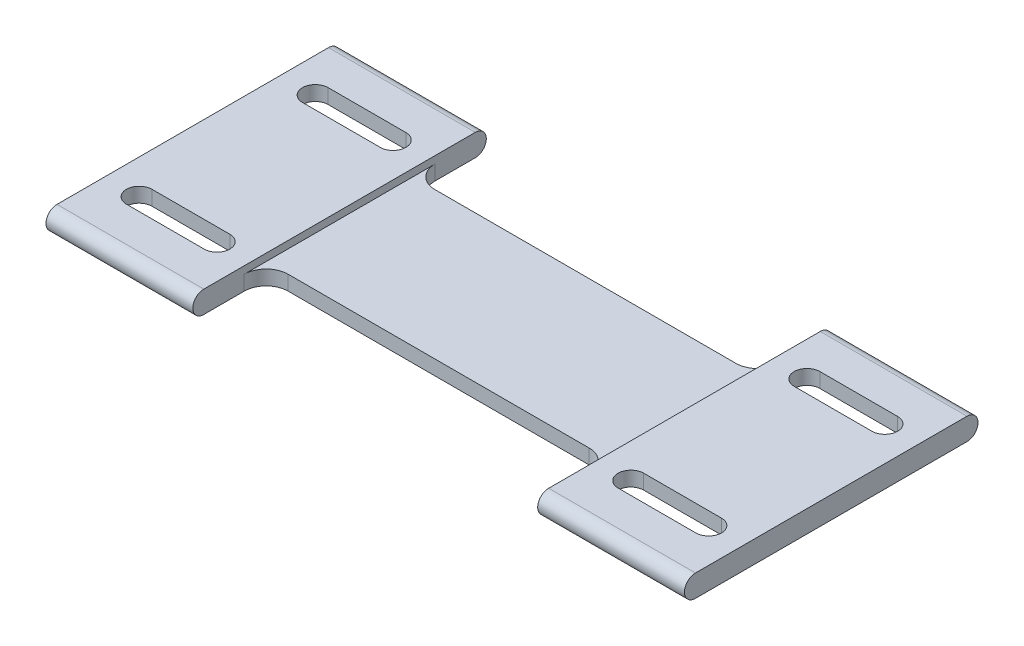
SolidWorks part; units mm, degrees
ref_plane "前视基准面" through (0, 0, 0) normal (0, 0, 1) x (1, 0, 0)
ref_plane "上视基准面" through (0, 0, 0) normal (0, 1, 0) x (1, 0, 0)
ref_plane "右视基准面" through (0, 0, 0) normal (1, 0, 0) x (0, 0, -1)
sketch "草图1" plane through (0, 0, 0) normal (0, 1, 0) x (1, 0, 0)
  line L1 (-43.5, -18.5) -> (43.5, -18.5) construction
  line L2 (-43.5, -18.5) -> (-43.5, 18.5) construction
  line L3 (-43.5, 18.5) -> (43.5, 18.5) construction
  line L4 (43.5, -18.5) -> (43.5, 18.5) construction
  line L5 (-43.5, -18.5) -> (43.5, 18.5) construction
  line L6 (-43.5, 18.5) -> (43.5, -18.5) construction
  point P0 (0, 0)
  dimension "D1" = 87
  dimension "D2" = 37
sketch "草图2" plane through (0, 0, 0) normal (1, 0, 0) x (0, 0, -1)
  line L0 (-18.5, 0) -> (18.5, 0) construction
  line L1 (-18.5, 0) -> (18.5, 0) construction
  line L2 (-18.5, 0) -> (18.5, 0) construction
  line L3 (18.5, 0) -> (-18.5, 0) construction
  line L4 (-18.5, 1.5) -> (18.5, 1.5)
  line L5 (-18.5, -1.5) -> (18.5, -1.5)
  arc A0 (-18.5, 1.5) -> (-18.5, -1.5) centre (-18.5, 0) ccw
  arc A1 (18.5, -1.5) -> (18.5, 1.5) centre (18.5, 0) ccw
  point P8 (0, 0)
  dimension "D1" = 1.5
extrude "凸台-拉伸1" add sketch "草图2" along normal mid plane 87
sketch "草图3" plane through (0, 1.5, 0) normal (0, 1, 0) x (1, 0, 0)
  line L0 (43.5, 20) -> (-43.5, 20) construction
  line L1 (-23.5, -20) -> (23.5, -20)
  line L2 (-23.5, -20) -> (-23.5, 20)
  line L3 (-23.5, 20) -> (23.5, 20)
  line L4 (23.5, -20) -> (23.5, 20)
  line L5 (-23.5, -20) -> (23.5, 20) construction
  line L6 (-23.5, 20) -> (23.5, -20) construction
  line L7 (-43.5, -18.5) -> (-43.5, 18.5) construction
  point P0 (0, 0)
  dimension "D1" = 20
extrude "切除-拉伸1" cut sketch "草图3" against normal blind 1
sketch "草图4" plane through (0, 0.5, 0) normal (0, 1, 0) x (1, 0, 0)
  line L0 (-43.5, -18.5) -> (43.5, 18.5) construction
  line L1 (-23.5, 9.9943) -> (23.5, 9.9943)
  line L2 (-23.5, 9.9943) -> (-23.5, 26.0227)
  line L3 (-23.5, 26.0227) -> (23.5, 26.0227)
  line L4 (23.5, 9.9943) -> (23.5, 26.0227)
  line L5 (-23.5, 9.9943) -> (23.5, 26.0227) construction
  line L6 (-23.5, 26.0227) -> (23.5, 9.9943) construction
  line L7 (-23.5, 0) -> (23.5, 0) construction
  line L8 (-23.5, -18.5) -> (-23.5, 18.5) construction
  line L9 (23.5, 18.5) -> (23.5, -18.5) construction
  line L10 (-23.5, -26.0227) -> (23.5, -9.9943) construction
  line L11 (-23.5, -9.9943) -> (23.5, -26.0227) construction
  line L12 (23.5, -9.9943) -> (23.5, -26.0227)
  line L13 (-23.5, -26.0227) -> (23.5, -26.0227)
  line L14 (-23.5, -9.9943) -> (-23.5, -26.0227)
  line L15 (-23.5, -9.9943) -> (23.5, -9.9943)
  line L16 (23.5, -19.9142) -> (23.5, 19.9142) construction
  line L17 (-23.5, 19.9142) -> (-23.5, -19.9142) construction
  point P0 (0, 18.0085)
  point P18 (0, -18.0085)
extrude "切除-拉伸2" cut sketch "草图4" against normal through all
sketch "草图5" plane through (0, -1.5, 0) normal (0, -1, 0) x (-1, 0, 0)
  line L0 (38.8, -12) -> (28.2, -12) construction
  line L1 (38.8, -13.75) -> (28.2, -13.75)
  line L2 (38.8, -10.25) -> (28.2, -10.25)
  line L3 (23.5, -20) -> (43.5, -20) construction
  line L4 (43.5, -18.5) -> (43.5, 18.5) construction
  line L5 (23.5, -9.9943) -> (23.5, -18.5) construction
  line L6 (43.5, 0) -> (-43.5, 0) construction
  line L7 (-43.5, -18.5) -> (-43.5, 18.5) construction
  line L8 (38.8, 12) -> (28.2, 12) construction
  line L9 (38.8, 13.75) -> (28.2, 13.75)
  line L10 (38.8, 10.25) -> (28.2, 10.25)
  line L11 (0, -9.9943) -> (0, 9.9943) construction
  line L12 (-23.5, -9.9943) -> (23.5, -9.9943) construction
  line L13 (23.5, 9.9943) -> (-23.5, 9.9943) construction
  line L14 (-38.8, 12) -> (-28.2, 12) construction
  line L15 (-38.8, 13.75) -> (-28.2, 13.75)
  line L16 (-38.8, 10.25) -> (-28.2, 10.25)
  line L17 (-38.8, -12) -> (-28.2, -12) construction
  line L18 (-38.8, -13.75) -> (-28.2, -13.75)
  line L19 (-38.8, -10.25) -> (-28.2, -10.25)
  arc A0 (38.8, -13.75) -> (38.8, -10.25) centre (38.8, -12) ccw
  arc A1 (28.2, -10.25) -> (28.2, -13.75) centre (28.2, -12) ccw
  arc A2 (38.8, 13.75) -> (38.8, 10.25) centre (38.8, 12) cw
  arc A3 (28.2, 10.25) -> (28.2, 13.75) centre (28.2, 12) cw
  arc A4 (-38.8, 13.75) -> (-38.8, 10.25) centre (-38.8, 12) ccw
  arc A5 (-28.2, 10.25) -> (-28.2, 13.75) centre (-28.2, 12) ccw
  arc A6 (-38.8, -13.75) -> (-38.8, -10.25) centre (-38.8, -12) cw
  arc A7 (-28.2, -10.25) -> (-28.2, -13.75) centre (-28.2, -12) cw
  point P2 (33.5, -12)
  point P19 (33.5, 12)
  point P32 (-33.5, 12)
  point P39 (-33.5, -12)
  dimension "D1" = 1.75
  dimension "D2" = 8
  dimension "D3" = 4.7
  dimension "D4" = 4.7
extrude "切除-拉伸3" cut sketch "草图5" against normal through all
sketch "草图6" plane through (0, -1.5, 0) normal (0, -1, 0) x (1, 0, 0)
  line L0 (-28.2, 15.75) -> (-38.8, 15.75)
  line L1 (-38.8, 8.25) -> (-28.2, 8.25)
  line L2 (-28.2, 13.75) -> (-38.8, 13.75)
  line L3 (-38.8, 10.25) -> (-28.2, 10.25)
  line L4 (-28.2, 13.75) -> (-38.8, 13.75) construction
  line L5 (-38.8, 10.25) -> (-28.2, 10.25) construction
  line L6 (-38.8, -13.75) -> (-28.2, -13.75)
  line L7 (-28.2, -10.25) -> (-38.8, -10.25)
  line L8 (-38.8, -13.75) -> (-28.2, -13.75) construction
  line L9 (-28.2, -10.25) -> (-38.8, -10.25) construction
  line L10 (38.8, 13.75) -> (28.2, 13.75)
  line L11 (28.2, 10.25) -> (38.8, 10.25)
  line L12 (38.8, 13.75) -> (28.2, 13.75) construction
  line L13 (28.2, 10.25) -> (38.8, 10.25) construction
  line L14 (28.2, -13.75) -> (38.8, -13.75)
  line L15 (38.8, -10.25) -> (28.2, -10.25)
  line L16 (28.2, -13.75) -> (38.8, -13.75) construction
  line L17 (38.8, -10.25) -> (28.2, -10.25) construction
  line L18 (-38.8, -15.75) -> (-28.2, -15.75)
  line L19 (-28.2, -8.25) -> (-38.8, -8.25)
  line L20 (38.8, 15.75) -> (28.2, 15.75)
  line L21 (28.2, 8.25) -> (38.8, 8.25)
  line L22 (28.2, -15.75) -> (38.8, -15.75)
  line L23 (38.8, -8.25) -> (28.2, -8.25)
  arc A0 (-38.8, 15.75) -> (-38.8, 8.25) centre (-38.8, 12) ccw
  arc A1 (-28.2, 8.25) -> (-28.2, 15.75) centre (-28.2, 12) ccw
  arc A2 (-28.2, 10.25) -> (-28.2, 13.75) centre (-28.2, 12) ccw
  arc A3 (-38.8, 13.75) -> (-38.8, 10.25) centre (-38.8, 12) ccw
  arc A4 (-28.2, 10.25) -> (-28.2, 13.75) centre (-28.2, 12) ccw construction
  arc A5 (-38.8, 13.75) -> (-38.8, 10.25) centre (-38.8, 12) ccw construction
  arc A6 (-28.2, -13.75) -> (-28.2, -10.25) centre (-28.2, -12) ccw
  arc A7 (-38.8, -10.25) -> (-38.8, -13.75) centre (-38.8, -12) ccw
  arc A8 (-28.2, -13.75) -> (-28.2, -10.25) centre (-28.2, -12) ccw construction
  arc A9 (-38.8, -10.25) -> (-38.8, -13.75) centre (-38.8, -12) ccw construction
  arc A10 (28.2, 13.75) -> (28.2, 10.25) centre (28.2, 12) ccw
  arc A11 (38.8, 10.25) -> (38.8, 13.75) centre (38.8, 12) ccw
  arc A12 (28.2, 13.75) -> (28.2, 10.25) centre (28.2, 12) ccw construction
  arc A13 (38.8, 10.25) -> (38.8, 13.75) centre (38.8, 12) ccw construction
  arc A14 (28.2, -10.25) -> (28.2, -13.75) centre (28.2, -12) ccw
  arc A15 (38.8, -13.75) -> (38.8, -10.25) centre (38.8, -12) ccw
  arc A16 (28.2, -10.25) -> (28.2, -13.75) centre (28.2, -12) ccw construction
  arc A17 (38.8, -13.75) -> (38.8, -10.25) centre (38.8, -12) ccw construction
  arc A18 (-28.2, -15.75) -> (-28.2, -8.25) centre (-28.2, -12) ccw
  arc A19 (-38.8, -8.25) -> (-38.8, -15.75) centre (-38.8, -12) ccw
  arc A20 (28.2, 15.75) -> (28.2, 8.25) centre (28.2, 12) ccw
  arc A21 (38.8, 8.25) -> (38.8, 15.75) centre (38.8, 12) ccw
  arc A22 (38.8, -15.75) -> (38.8, -8.25) centre (38.8, -12) ccw
  arc A23 (28.2, -8.25) -> (28.2, -15.75) centre (28.2, -12) ccw
  dimension "D1" = 0
  dimension "D2" = 0
  dimension "D3" = 0
  dimension "D4" = 0
  dimension "D5" = 2
extrude "切除-拉伸4" cut sketch "草图6" against normal blind 1
fillet "圆角1" radius 3 4 edges at (23.5, -0.5, 9.9943) (-23.5, -0.5, 9.9943) (23.5, -0.5, -9.9943) (-23.5, -0.5, -9.9943)
sketch "草图7" plane through (0, 0.5, 0) normal (0, 1, 0) x (1, 0, 0)
  line L1 (-16.5, -15.1974) -> (16.5, -15.1974)
  line L2 (-16.5, -15.1974) -> (-16.5, 15.1974)
  line L3 (-16.5, 15.1974) -> (16.5, 15.1974)
  line L4 (16.5, -15.1974) -> (16.5, 15.1974)
  line L5 (-16.5, -15.1974) -> (16.5, 15.1974) construction
  line L6 (-16.5, 15.1974) -> (16.5, -15.1974) construction
  point P0 (0, 0)
  dimension "D1" = 33
